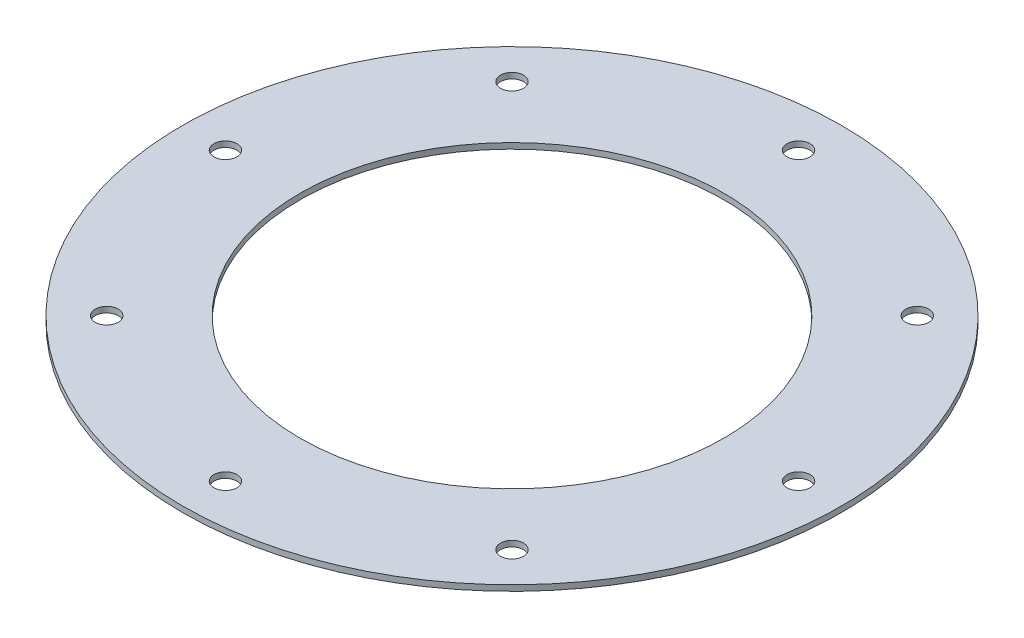
SolidWorks part; units mm, degrees
material "Plain Carbon Steel"
ref_plane "Front Plane" through (0, 0, 0) normal (0, 0, 1) x (1, 0, 0)
ref_plane "Top Plane" through (0, 0, 0) normal (0, 1, 0) x (1, 0, 0)
ref_plane "Right Plane" through (0, 0, 0) normal (1, 0, 0) x (0, 0, -1)
sketch "Sketch1" plane through (0, 0, 0) normal (0, 1, 0) x (1, 0, 0)
  line L0 (0, 0) -> (-131.934, 0) construction
  circle A0 centre (0, 0) radius 115
  circle A1 centre (0, 0) radius 74
  circle A2 centre (-100, 0) radius 4
  circle A3 centre (-70.7107, 70.7107) radius 4
  circle A4 centre (0, 100) radius 4
  circle A5 centre (70.7107, 70.7107) radius 4
  circle A6 centre (100, 0) radius 4
  circle A7 centre (70.7107, -70.7107) radius 4
  circle A8 centre (0, -100) radius 4
  circle A9 centre (-70.7107, -70.7107) radius 4
  point P24 (0, 0)
  dimension "D1" = 148
  dimension "D2" = 230
  dimension "D3" = 8
  dimension "D4" = 100
  dimension "D5" = 8
extrude "Boss-Extrude1" add sketch "Sketch1" along normal blind 2
